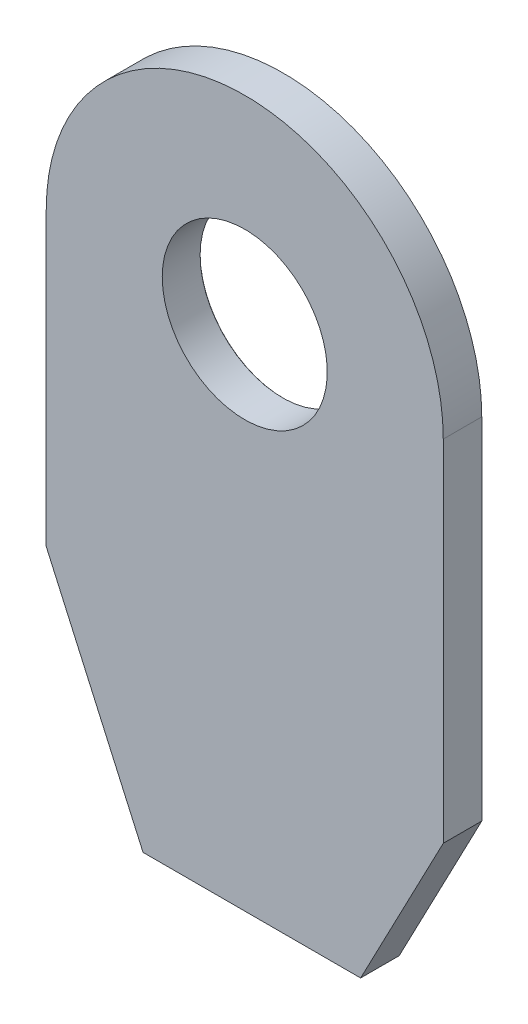
SolidWorks part; units mm, degrees
ref_plane "Front Plane" through (0, 0, 0) normal (0, 0, 1) x (1, 0, 0)
ref_plane "Top Plane" through (0, 0, 0) normal (0, 1, 0) x (1, 0, 0)
ref_plane "Right Plane" through (0, 0, 0) normal (1, 0, 0) x (0, 0, -1)
sketch "Sketch1" plane through (0, 0, 0) normal (0, 0, 1) x (1, 0, 0)
  line L0 (-7.94, 0) -> (-7.94, -20.32)
  line L1 (-7.94, -20.32) -> (7.94, -20.32)
  line L2 (7.94, -20.32) -> (7.94, 0)
  line L3 (7.94, -14.0013) -> (4.6346, -20.32)
  line L4 (-4.0681, -20.32) -> (-7.94, -11.6613)
  circle A0 centre (0, 0) radius 7.94
  dimension "D1" = 15.88
  dimension "D2" = 20.32
extrude "Boss-Extrude1" add sketch "Sketch1" along normal blind 1.54 contours A0 L0 L1 L2
sketch "Sketch4" plane through (0, 0, 0) normal (0, 0, -1) x (-1, 0, 0)
  point P0 (0, 0)
hole_wizard "M6 Clearance Hole1" positions "Sketch4" profile "Sketch3" hole size "M6" standard "ANSI Metric" end condition through all
sketch "Sketch3" plane through (0, 0, 0) normal (1, 0, 0) x (0, 1, 0)
  line L0 (0, 0) -> (0, 1.54)
  line L1 (0, 1.54) -> (3.3, 1.54)
  line L2 (3.3, 1.54) -> (3.3, 0.025)
  line L3 (3.3, 0.025) -> (3.325, 0)
  line L5 (3.325, 0) -> (0, 0)
  line L6 (-3.3, 0.025) -> (-3.325, 0) construction
  line L11 (0, -6.35) -> (0, 107.95) construction
  dimension "Thru Hole Dia." = 6.6
  dimension "Thru Hole Depth" = 1.54
  dimension "Near C'Sink Dia." = 6.65
  dimension "Near C'Sink Angle" = 90
